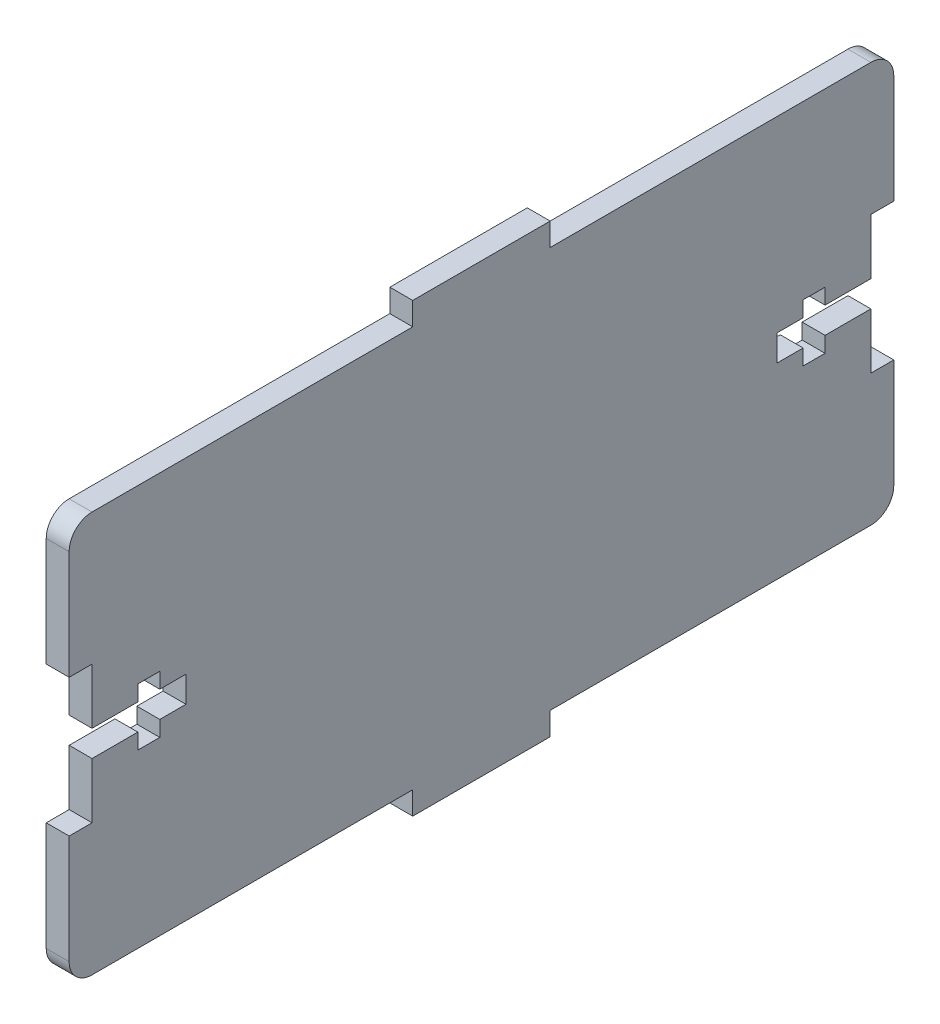
SolidWorks part; units mm, degrees
ref_plane "Front Plane" through (0, 0, 0) normal (0, 0, 1) x (1, 0, 0)
ref_plane "Top Plane" through (0, 0, 0) normal (0, 1, 0) x (1, 0, 0)
ref_plane "Right Plane" through (0, 0, 0) normal (1, 0, 0) x (0, 0, -1)
sketch "Sketch2" plane through (0, 0, 0) normal (1, 0, 0) x (0, 0, -1)
  line L0 (-45.72, 22.225) -> (-45.72, 7.62)
  line L1 (-45.72, 22.225) -> (45.72, 22.225) construction
  line L2 (-45.72, 22.225) -> (-45.72, -22.225) construction
  line L3 (-45.72, -22.225) -> (45.72, -22.225) construction
  line L4 (45.72, 22.225) -> (45.72, -22.225) construction
  line L5 (-45.72, 22.225) -> (45.72, -22.225) construction
  line L6 (-45.72, -22.225) -> (45.72, 22.225) construction
  line L7 (-45.72, 7.62) -> (-43.18, 7.62)
  line L8 (-43.18, 7.62) -> (-43.18, -7.62) construction
  line L9 (-43.18, -7.62) -> (-45.72, -7.62)
  line L10 (-45.72, -7.62) -> (-45.72, -22.225)
  line L11 (0, 22.225) -> (0, -22.225) construction
  line L12 (-45.72, 0) -> (45.72, 0) construction
  line L13 (43.18, -7.62) -> (45.72, -7.62)
  line L14 (43.18, 7.62) -> (43.18, -7.62) construction
  line L15 (45.72, 7.62) -> (43.18, 7.62)
  line L16 (-45.72, -22.225) -> (-7.62, -22.225)
  line L17 (-7.62, -22.225) -> (-7.62, -24.765)
  line L18 (-7.62, -24.765) -> (7.62, -24.765)
  line L19 (7.62, -24.765) -> (7.62, -22.225)
  line L20 (7.62, -22.225) -> (45.72, -22.225)
  line L21 (45.72, -22.225) -> (45.72, -7.62)
  line L22 (45.72, 7.62) -> (45.72, 22.225)
  line L23 (7.62, 24.765) -> (7.62, 22.225)
  line L24 (-7.62, 24.765) -> (7.62, 24.765)
  line L25 (-7.62, 22.225) -> (-7.62, 24.765)
  line L26 (45.72, 22.225) -> (7.62, 22.225)
  line L27 (-7.62, 22.225) -> (-45.72, 22.225)
  line L28 (-43.18, 7.62) -> (-43.18, 1.4478)
  line L29 (-43.18, 1.4478) -> (-38.1, 1.4478)
  line L30 (-38.1, 1.4478) -> (-38.1, 3.175)
  line L31 (-38.1, 3.175) -> (-35.6679, 3.175)
  line L32 (-35.6679, 3.175) -> (-35.6679, 1.4478)
  line L33 (-35.6679, 1.4478) -> (-32.766, 1.4478)
  line L34 (-32.766, 1.4478) -> (-32.766, -1.4478)
  line L35 (-38.1, -3.175) -> (-35.6679, -3.175)
  line L36 (-35.6679, -1.4478) -> (-32.766, -1.4478)
  line L37 (-35.6679, -3.175) -> (-35.6679, -1.4478)
  line L38 (-38.1, -1.4478) -> (-38.1, -3.175)
  line L39 (-43.18, -1.4478) -> (-38.1, -1.4478)
  line L40 (-43.18, -7.62) -> (-43.18, -1.4478)
  line L41 (43.18, -7.62) -> (43.18, -1.4478)
  line L42 (43.18, -1.4478) -> (38.1, -1.4478)
  line L43 (38.1, -1.4478) -> (38.1, -3.175)
  line L44 (38.1, -3.175) -> (35.6679, -3.175)
  line L45 (35.6679, -3.175) -> (35.6679, -1.4478)
  line L46 (35.6679, -1.4478) -> (32.766, -1.4478)
  line L47 (32.766, 1.4478) -> (32.766, -1.4478)
  line L48 (35.6679, 1.4478) -> (32.766, 1.4478)
  line L49 (35.6679, 3.175) -> (35.6679, 1.4478)
  line L50 (38.1, 3.175) -> (35.6679, 3.175)
  line L51 (38.1, 1.4478) -> (38.1, 3.175)
  line L52 (43.18, 1.4478) -> (38.1, 1.4478)
  line L53 (43.18, 7.62) -> (43.18, 1.4478)
  point P0 (0, 0)
  point P36 (-32.766, 0)
  dimension "D1" = 91.44
  dimension "D2" = 44.45
  dimension "D3" = 15.24
  dimension "D4" = 2.54
  dimension "D5" = 15.24
  dimension "D6" = 2.54
  dimension "D7" = 12.954
  dimension "D8" = 5.08
  dimension "D9" = 2.432
  dimension "D10" = 6.35
  dimension "D11" = 2.8956
extrude "Boss-Extrude1" add sketch "Sketch2" along normal blind 2.54
fillet "Fillet1" radius 2.54 4 edges at (1.27, -22.225, 45.72) (1.27, -22.225, -45.72) (1.27, 22.225, -45.72) (1.27, 22.225, 45.72)
